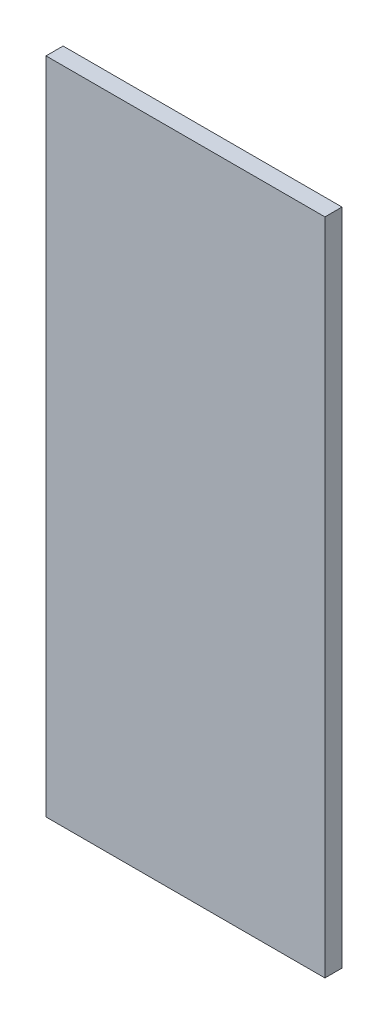
SolidWorks part; units mm, degrees
ref_plane "Plan de face" through (0, 0, 0) normal (0, 0, 1) x (1, 0, 0)
ref_plane "Plan de dessus" through (0, 0, 0) normal (0, 1, 0) x (1, 0, 0)
ref_plane "Plan de droite" through (0, 0, 0) normal (1, 0, 0) x (0, 0, -1)
sketch "Esquisse1" plane through (0, 0, 0) normal (0, 0, 1) x (1, 0, 0)
  line L1 (0, 0) -> (245, 0)
  line L2 (0, 0) -> (0, 579)
  line L3 (0, 579) -> (245, 579)
  line L4 (245, 0) -> (245, 579)
  dimension "D1" = 245
  dimension "D2" = 579
extrude "Boss.-Extru.1" add sketch "Esquisse1" along normal blind 15
